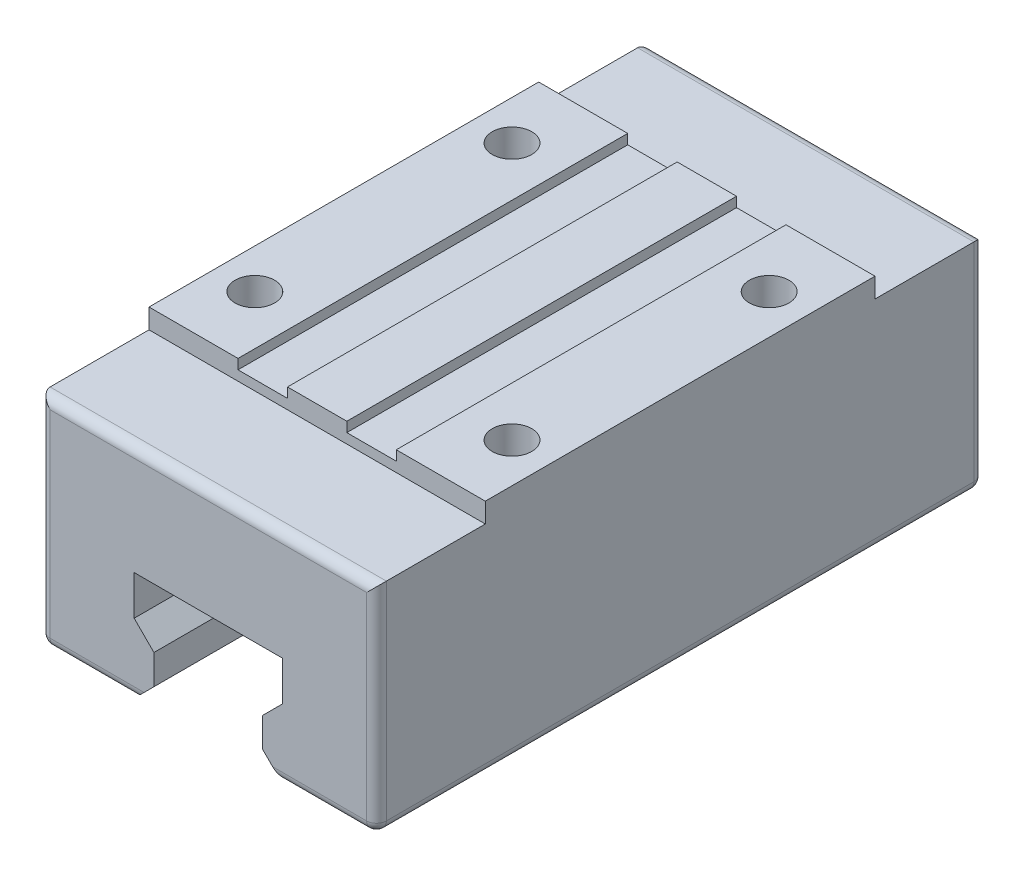
SolidWorks part; units mm, degrees
ref_plane "Front Plane" through (0, 0, 0) normal (0, 0, 1) x (1, 0, 0)
ref_plane "Top Plane" through (0, 0, 0) normal (0, 1, 0) x (1, 0, 0)
ref_plane "Right Plane" through (0, 0, 0) normal (1, 0, 0) x (0, 0, -1)
sketch "Sketch1" plane through (0, 0, 0) normal (0, 0, 1) x (1, 0, 0)
  line L0 (0, 29.7182) -> (0, -6.39) construction
  line L2 (7.5, 0) -> (7.5, 4)
  line L3 (7.5, 4) -> (5.5, 6)
  line L4 (5.5, 6) -> (5.5, 9)
  line L5 (5.5, 9) -> (7.5, 11)
  line L6 (7.5, 11) -> (7.5, 15)
  line L13 (7.5, 15) -> (-7.5, 15)
  line L14 (-7.5, 0) -> (7.5, 0)
  line L15 (7.5, 4) -> (17, 4)
  line L16 (17, 4) -> (17, 26)
  line L17 (17, 26) -> (-17, 26)
  line L18 (-17, 4) -> (-17, 26)
  line L19 (-7.5, 4) -> (-17, 4)
  line L20 (-7.5, 11) -> (-7.5, 15)
  line L21 (-5.5, 9) -> (-7.5, 11)
  line L22 (-5.5, 6) -> (-5.5, 9)
  line L23 (-7.5, 4) -> (-5.5, 6)
  line L24 (-7.5, 0) -> (-7.5, 4)
  point P9 (0, 15)
  point P15 (0, 0)
  point P20 (0, 26)
  point P23 (0, 0)
  point P24 (0, 15)
  dimension "D1" = 7.5
  dimension "D2" = 15
  dimension "D3" = 4
  dimension "D4" = 4
  dimension "D5" = 45
  dimension "D6" = 45
  dimension "D7" = 3
  dimension "D8" = 17
  dimension "D9" = 26
extrude "Boss-Extrude1" add sketch "Sketch1" along normal mid plane 61.4 contours L0 L17 L18 L19 L23 L22 L21 L20 L13 | L17 L0 L13 L6 L5 L4 L3 L15 L16
sketch "Sketch4" plane through (0, 26, 0) normal (0, 1, 0) x (1, 0, 0)
  line L0 (0, 19.7) -> (0, -19.7) construction
  line L1 (-17, -19.7) -> (17, -19.7)
  line L2 (-17, -19.7) -> (-17, 19.7)
  line L3 (-17, 19.7) -> (17, 19.7)
  line L4 (17, -19.7) -> (17, 19.7)
  line L5 (-17, -19.7) -> (17, 19.7) construction
  line L6 (-17, 19.7) -> (17, -19.7) construction
  line L7 (-17, 0) -> (17, 0) construction
  circle A0 centre (-13, 13) radius 2
  circle A1 centre (13, 13) radius 2
  circle A2 centre (-13, -13) radius 2
  circle A3 centre (13, -13) radius 2
  point P0 (0, 0)
  dimension "D5" = 4
  dimension "D1" = 34
  dimension "D2" = 39.4
  dimension "D3" = 13
  dimension "D4" = 13
extrude "Boss-Extrude2" add sketch "Sketch4" along normal blind 2
sketch "Sketch5" plane through (0, 28, 0) normal (0, 1, 0) x (1, 0, 0)
  line L0 (0, 22.6553) -> (0, -21.83) construction
  line L1 (-8, 19.7) -> (-8, -19.7)
  line L2 (17, 19.7) -> (-17, 19.7) construction
  line L3 (-17, -19.7) -> (17, -19.7) construction
  line L4 (-8, -19.7) -> (-3, -19.7)
  line L5 (-3, -19.7) -> (-3, 19.7)
  line L6 (-3, 19.7) -> (-8, 19.7)
  line L7 (3, 19.7) -> (8, 19.7)
  line L8 (3, -19.7) -> (3, 19.7)
  line L9 (8, -19.7) -> (3, -19.7)
  line L10 (8, 19.7) -> (8, -19.7)
  dimension "D1" = 5
  dimension "D2" = 3
extrude "Cut-Extrude1" cut sketch "Sketch5" against normal blind 1
fillet "Fillet1" radius 1 2 edges at (-17, 4, 0) (17, 4, 0)
fillet "Fillet2" radius 1 14 edges at (11.75, 4, -30.7) (11.75, 4, 30.7) (16.7071, 4.2929, 30.7) (16.7071, 4.2929, -30.7) (-11.75, 4, 30.7) (-11.75, 4, -30.7) (-16.7071, 4.2929, 30.7) (-16.7071, 4.2929, -30.7) (0, 26, 30.7) (0, 26, -30.7) (17, 15.5, 30.7) (17, 15.5, -30.7) (-17, 15.5, -30.7) (-17, 15.5, 30.7)
sketch "Sketch6" plane through (0, 28, 0) normal (0, 1, 0) x (1, 0, 0)
  circle A0 centre (-13, -13) radius 2 construction
  circle A1 centre (13, -13) radius 2 construction
  circle A2 centre (13, 13) radius 2 construction
  circle A3 centre (-13, 13) radius 2 construction
  circle A4 centre (-13, -13) radius 2
  circle A5 centre (13, -13) radius 2
  circle A6 centre (13, 13) radius 2
  circle A7 centre (-13, 13) radius 2
extrude "Cut-Extrude2" cut sketch "Sketch6" against normal blind 5.95
